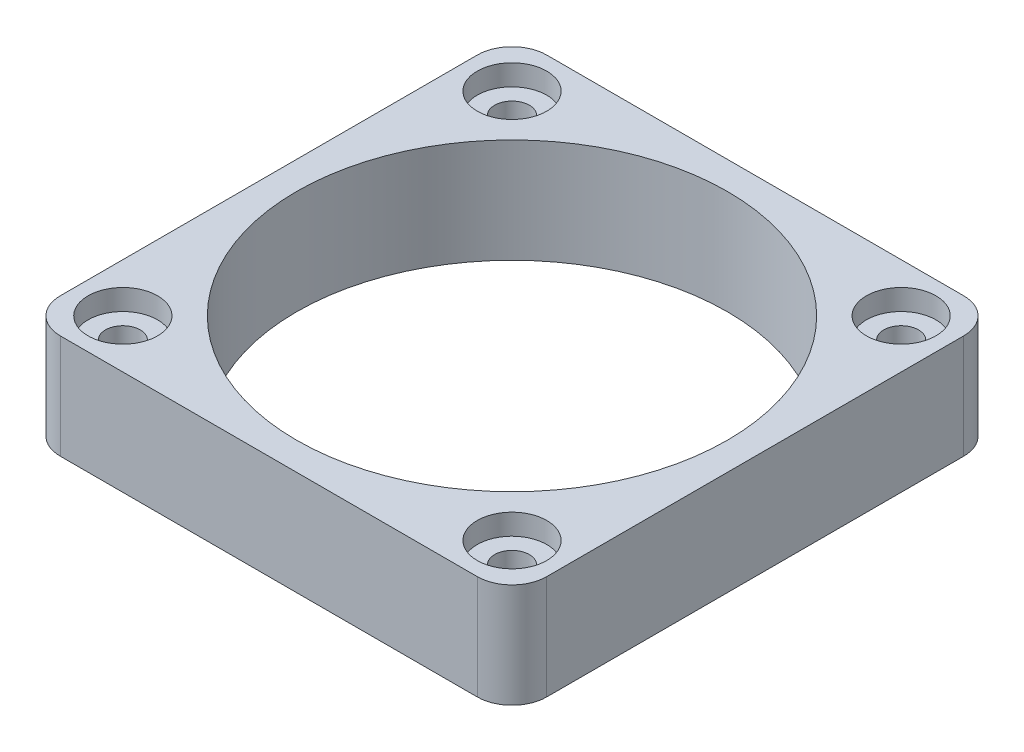
SolidWorks part; units mm, degrees
ref_plane "Front Plane" through (0, 0, 0) normal (0, 0, 1) x (1, 0, 0)
ref_plane "Top Plane" through (0, 0, 0) normal (0, 1, 0) x (1, 0, 0)
ref_plane "Right Plane" through (0, 0, 0) normal (1, 0, 0) x (0, 0, -1)
sketch "Sketch1" plane through (0, 0, 0) normal (0, 1, 0) x (1, 0, 0)
  line L1 (-35, 35) -> (35, 35)
  line L2 (-35, 35) -> (-35, -35)
  line L3 (-35, -35) -> (35, -35)
  line L4 (35, 35) -> (35, -35)
  line L5 (-35, 35) -> (35, -35) construction
  line L6 (-35, -35) -> (35, 35) construction
  circle A0 centre (0, 0) radius 31
  point P0 (0, 0)
  dimension "D2" = 62
  dimension "D1" = 70
extrude "Boss-Extrude1" add sketch "Sketch1" along normal blind 15
sketch "Sketch2" plane through (0, 15, 0) normal (0, 1, 0) x (1, 0, 0)
  line L0 (0, 35) -> (0, -35) construction
  line L1 (35, 35) -> (-35, 35) construction
  line L2 (-35, -35) -> (35, -35) construction
  line L3 (-35, 0) -> (35, 0) construction
  line L4 (-35, 35) -> (-35, -35) construction
  line L5 (35, -35) -> (35, 35) construction
  circle A0 centre (-28, 28) radius 2.5
  circle A1 centre (28, 28) radius 2.5
  circle A2 centre (28, -28) radius 2.5
  circle A3 centre (-28, -28) radius 2.5
  dimension "D1" = 5
  dimension "D2" = 7
  dimension "D3" = 7
extrude "Cut-Extrude1" cut sketch "Sketch2" against normal through all
fillet "Fillet1" radius 5 4 edges at (-35, 7.5, -35) (35, 7.5, -35) (35, 7.5, 35) (-35, 7.5, 35)
sketch "Sketch3" plane through (0, 15, 0) normal (0, 1, 0) x (1, 0, 0)
  line L0 (-35, 0) -> (35, 0) construction
  line L1 (-35, 30) -> (-35, -30) construction
  line L2 (35, -30) -> (35, 30) construction
  line L3 (0, -35) -> (0, 35) construction
  line L4 (-30, -35) -> (30, -35) construction
  line L5 (30, 35) -> (-30, 35) construction
  circle A0 centre (-28, 28) radius 5
  circle A1 centre (-28, -28) radius 5
  circle A2 centre (28, 28) radius 5
  circle A3 centre (28, -28) radius 5
  dimension "D1" = 10
extrude "Cut-Extrude2" cut sketch "Sketch3" against normal blind 3
